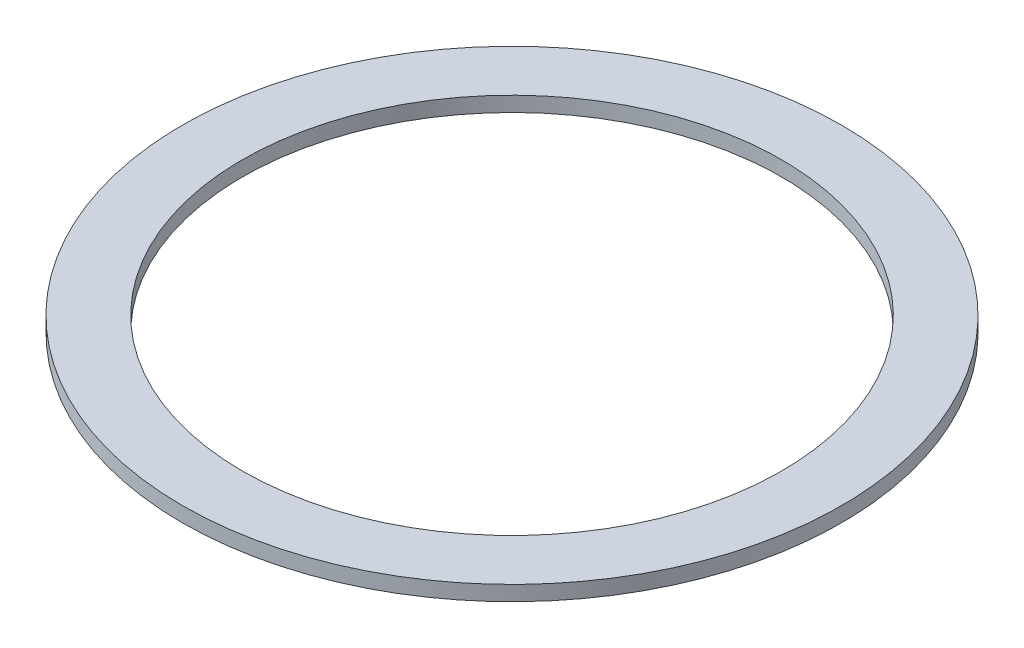
SolidWorks part; units mm, degrees
ref_plane "Front Plane" through (0, 0, 0) normal (0, 0, 1) x (1, 0, 0)
ref_plane "Top Plane" through (0, 0, 0) normal (0, 1, 0) x (1, 0, 0)
ref_plane "Right Plane" through (0, 0, 0) normal (1, 0, 0) x (0, 0, -1)
sketch "Sketch1" plane through (0, 0, 0) normal (0, 1, 0) x (1, 0, 0)
  circle A0 centre (0, 0) radius 69.85
  circle A1 centre (0, 0) radius 57.15
  dimension "D1" = 139.7
  dimension "D2" = 114.3
extrude "Boss-Extrude1" add sketch "Sketch1" along normal blind 3.175
